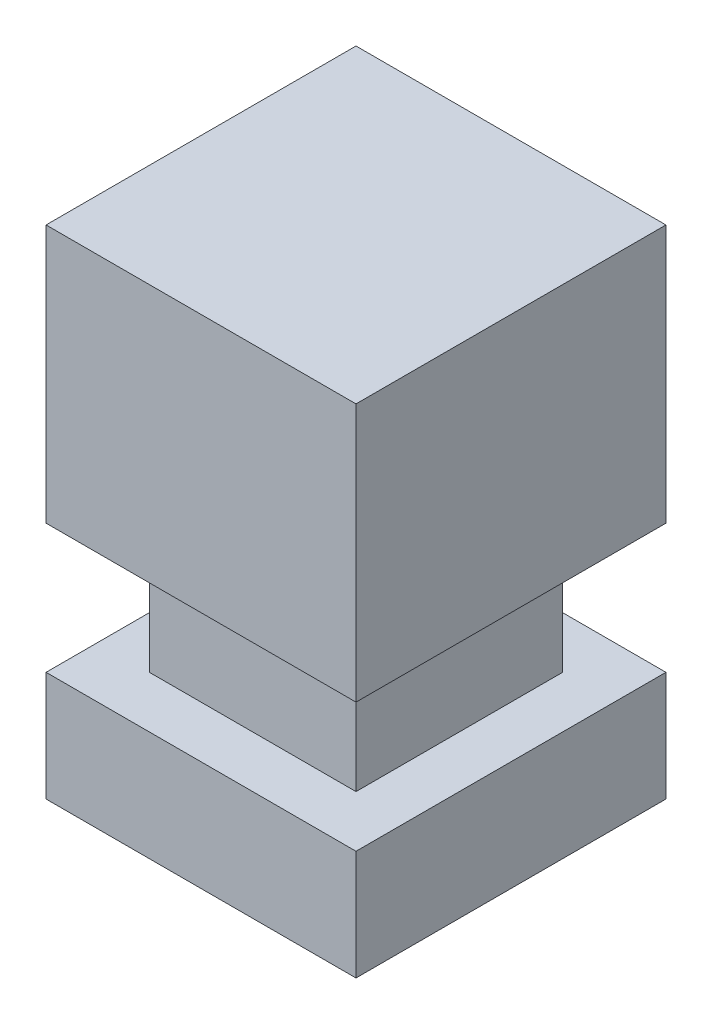
SolidWorks part; units mm, degrees
ref_plane "Front Plane" through (0, 0, 0) normal (0, 0, 1) x (1, 0, 0)
ref_plane "Top Plane" through (0, 0, 0) normal (0, 1, 0) x (1, 0, 0)
ref_plane "Right Plane" through (0, 0, 0) normal (1, 0, 0) x (0, 0, -1)
sketch "Sketch3" plane through (0, 0, 0) normal (0, 1, 0) x (1, 0, 0)
  line L1 (-1.2, -1.2) -> (1.2, -1.2)
  line L2 (-1.2, -1.2) -> (-1.2, 1.2)
  line L3 (-1.2, 1.2) -> (1.2, 1.2)
  line L4 (1.2, -1.2) -> (1.2, 1.2)
  line L5 (-1.2, -1.2) -> (1.2, 1.2) construction
  line L6 (-1.2, 1.2) -> (1.2, -1.2) construction
  point P0 (0, 0)
  dimension "D1" = 2.4
  dimension "D2" = 2.4
extrude "Boss-Extrude3" add sketch "Sketch3" against normal blind 3.85
sketch "Sketch8" plane through (0, 0, 1.2) normal (0, 0, 1) x (1, 0, 0)
  line L0 (-1.2, -2) -> (-1.2, -3)
  line L1 (-1.2, -2) -> (-0.8, -2)
  line L2 (-1.2, -3) -> (-0.8, -3)
  line L3 (-0.8, -2) -> (-0.8, -3)
  line L4 (-1.2, -3.85) -> (-1.2, 0) construction
  line L5 (-1.2, 0) -> (1.2, 0) construction
  line L6 (0, 0) -> (0, -3.85) construction
  line L7 (-1.2, -3.85) -> (1.2, -3.85) construction
  line L8 (0.8, -2) -> (0.8, -3)
  line L9 (1.2, -3) -> (0.8, -3)
  line L10 (1.2, -2) -> (0.8, -2)
  line L11 (1.2, -2) -> (1.2, -3)
  point P6 (-1.2, -2.5)
  dimension "D1" = 1
  dimension "D2" = 0.4
  dimension "D3" = 2.5
sketch "Sketch10" plane through (1.2, 0, 0) normal (-1, 0, 0) x (0, 0, 1)
  line L0 (-1.2, -2) -> (-1.2, -3)
  line L1 (-1.2, -2) -> (-0.8, -2)
  line L2 (-1.2, -3) -> (-0.8, -3)
  line L3 (-0.8, -2) -> (-0.8, -3)
  line L6 (0, 0) -> (0, -3.85) construction
  line L8 (0.8, -2) -> (0.8, -3)
  line L9 (1.2, -3) -> (0.8, -3)
  line L10 (1.2, -2) -> (0.8, -2)
  line L11 (1.2, -2) -> (1.2, -3)
extrude "Cut-Extrude1" cut sketch "Sketch8" against normal blind 2.4
extrude "Cut-Extrude2" cut sketch "Sketch10" along normal blind 2.4
equation "\"D\"= 2.4mm"
equation "\"D1@Sketch3\"=\"D\""
equation "\"D2@Sketch3\"=\"D\""
equation "\"D1@Cut-Extrude1\"=\"D\""
equation "\"D1@Cut-Extrude2\"=\"D\""
